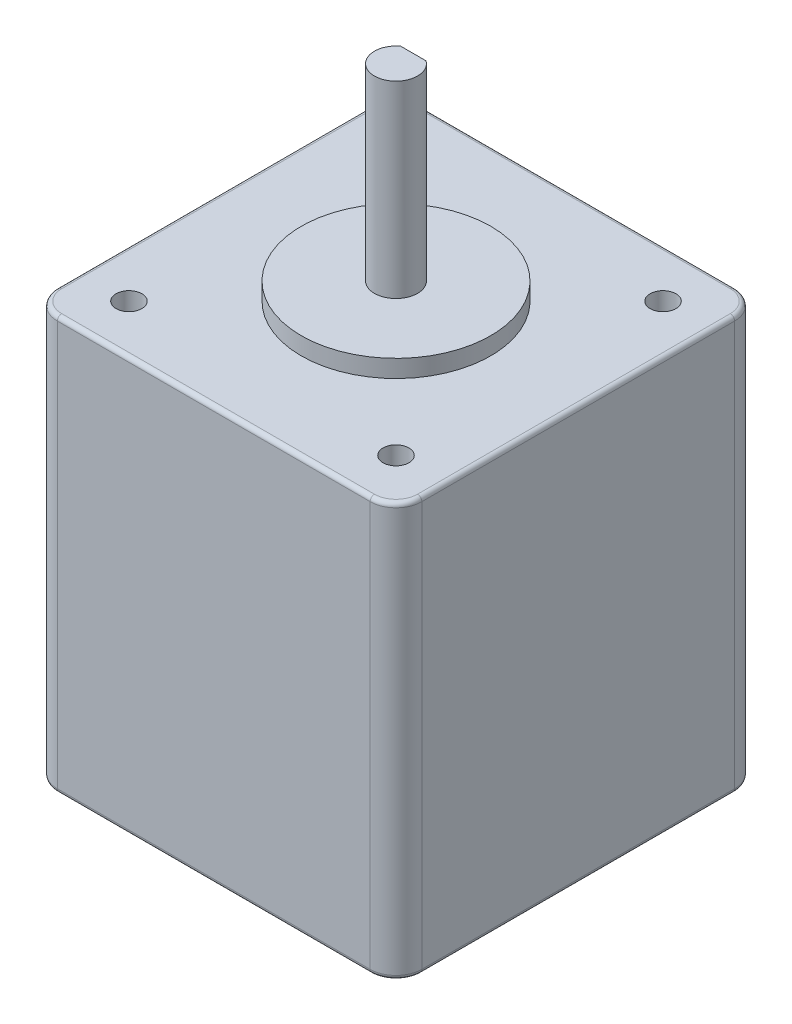
SolidWorks part; units mm, degrees
ref_plane "Front Plane" through (0, 0, 0) normal (0, 0, 1) x (1, 0, 0)
ref_plane "Top Plane" through (0, 0, 0) normal (0, 1, 0) x (1, 0, 0)
ref_plane "Right Plane" through (0, 0, 0) normal (1, 0, 0) x (0, 0, -1)
sketch "Sketch2" plane through (0, 0, 0) normal (0, 1, 0) x (1, 0, 0)
  line L0 (0, 42.3) -> (5.655, 36.645) construction
  line L1 (0, 0) -> (42.3, 0)
  line L2 (0, 0) -> (0, 42.3)
  line L3 (0, 42.3) -> (42.3, 42.3)
  line L4 (42.3, 0) -> (42.3, 42.3)
  line L5 (5.655, 36.645) -> (36.645, 36.645) construction
  line L6 (5.655, 36.645) -> (5.655, 5.655) construction
  line L7 (5.655, 5.655) -> (36.645, 5.655) construction
  line L8 (36.645, 36.645) -> (36.645, 5.655) construction
  line L9 (36.645, 5.655) -> (42.3, 0) construction
  line L10 (36.645, 36.645) -> (42.3, 42.3) construction
  line L11 (0, 0) -> (5.655, 5.655) construction
  circle A0 centre (5.655, 36.645) radius 1.5
  circle A1 centre (36.645, 36.645) radius 1.5
  circle A2 centre (36.645, 5.655) radius 1.5
  circle A3 centre (5.655, 5.655) radius 1.5
  dimension "D3" = 3
  dimension "D1" = 42.3
  dimension "D2" = 30.99
extrude "Boss-Extrude1" add sketch "Sketch2" along normal blind 48
sketch "Sketch3" plane through (0, 48, 0) normal (0, 1, 0) x (1, 0, 0)
  line L0 (0, 42.3) -> (42.3, 0) construction
  circle A0 centre (21.15, 21.15) radius 11
  point P6 (21.15, 21.15)
  dimension "D1" = 22
extrude "Boss-Extrude2" add sketch "Sketch3" along normal blind 2.03
sketch "Sketch4" plane through (0, 50.03, 0) normal (0, 1, 0) x (1, 0, 0)
  circle A0 centre (21.15, 21.15) radius 2.5
  circle A1 centre (21.15, 21.15) radius 11 construction
  dimension "D1" = 5
extrude "Boss-Extrude3" add sketch "Sketch4" along normal blind 21.85
sketch "Sketch5" plane through (0, 71.88, 0) normal (0, 1, 0) x (1, 0, 0)
  line L0 (19.677, 23.17) -> (22.623, 23.17)
  circle A0 centre (21.15, 21.15) radius 2.5 construction
  arc A1 (19.677, 23.17) -> (22.623, 23.17) centre (21.15, 21.15) cw
  dimension "D1" = 4.52
extrude "Cut-Extrude1" cut sketch "Sketch5" against normal blind 14.86
fillet "Fillet1" radius 3 4 edges at (0, 24, -42.3) (42.3, 24, -42.3) (42.3, 24, 0) (0, 24, 0)
fillet "Fillet2" radius 0.5 16 edges at (0.8787, 0, -0.8787) (0, 0, -21.15) (0.8787, 0, -41.4213) (21.15, 0, -42.3) (41.4213, 0, -41.4213) (42.3, 0, -21.15) (41.4213, 0, -0.8787) (0.8787, 48, -0.8787) (0, 48, -21.15) (0.8787, 48, -41.4213) (21.15, 48, -42.3) (41.4213, 48, -41.4213) (42.3, 48, -21.15) (41.4213, 48, -0.8787) (21.15, 0, 0) (21.15, 48, 0)
